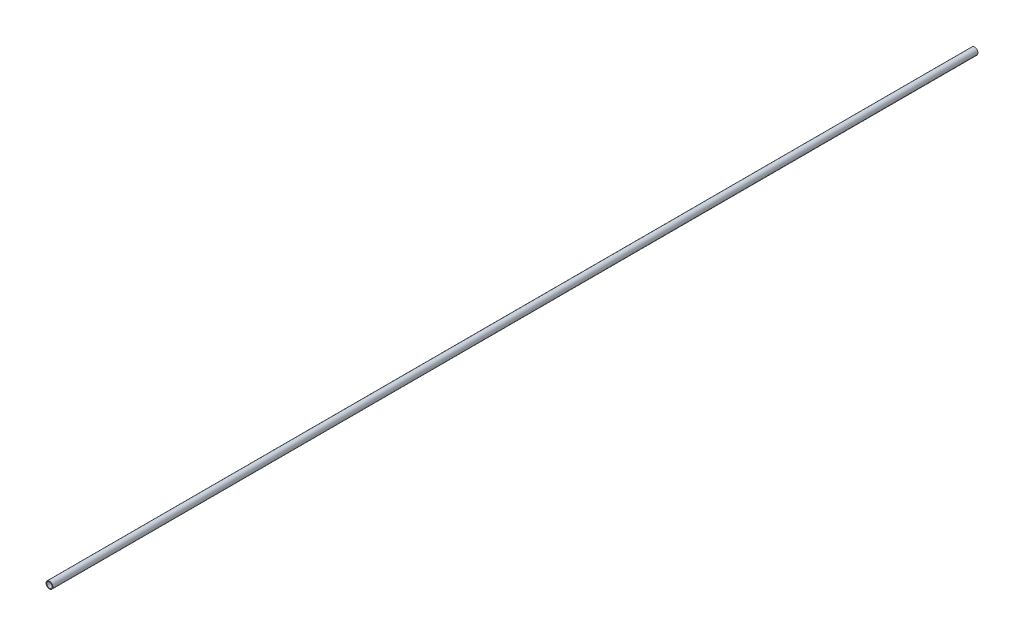
SolidWorks part; units mm, degrees
ref_plane "Спереди" through (0, 0, 0) normal (0, 0, 1) x (1, 0, 0)
ref_plane "Сверху" through (0, 0, 0) normal (0, 1, 0) x (1, 0, 0)
ref_plane "Справа" through (0, 0, 0) normal (1, 0, 0) x (0, 0, -1)
sketch "Эскиз1" plane through (0, 0, 0) normal (0, 0, 1) x (1, 0, 0)
  circle A0 centre (0, 0) radius 5
  circle A1 centre (0, 0) radius 4
  dimension "D1" = 10
  dimension "D2" = 8
extrude "Бобышка-Вытянуть1" add sketch "Эскиз1" along normal blind 1350
